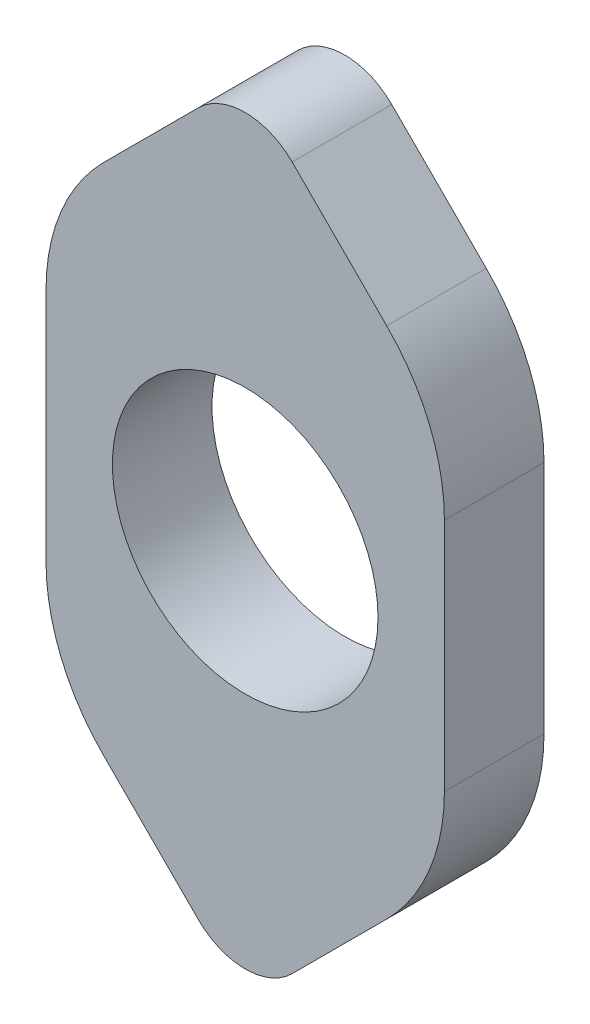
SolidWorks part; units mm, degrees
ref_plane "Спереди" through (0, 0, 0) normal (0, 0, 1) x (1, 0, 0)
ref_plane "Сверху" through (0, 0, 0) normal (0, 1, 0) x (1, 0, 0)
ref_plane "Справа" through (0, 0, 0) normal (1, 0, 0) x (0, 0, -1)
sketch "Эскиз1" plane through (0, 0, 0) normal (0, 0, 1) x (1, 0, 0)
  line L0 (1.1624, 13.6702) -> (1.1624, 2.4987) construction
  line L5 (-1.8376, 9.8546) -> (-1.8376, 6.3143)
  line L8 (4.1624, 9.8546) -> (4.1624, 6.3143)
  line L13 (1.8695, 13.3774) -> (3.2927, 11.9541)
  line L14 (1.8695, 2.7916) -> (3.2927, 4.2148)
  line L15 (0.4553, 13.3774) -> (-0.968, 11.9541)
  line L16 (0.4553, 2.7916) -> (-0.968, 4.2148)
  line L17 (1.1624, 14.0845) -> (1.1624, 2.0845) construction
  line L18 (4.1624, 14.0845) -> (4.1624, 2.0845) construction
  line L19 (-1.8376, 14.0845) -> (-1.8376, 2.0845) construction
  circle A7 centre (1.1624, 8.0845) radius 2
  arc A9 (1.8695, 13.3774) -> (0.4553, 13.3774) centre (1.1624, 12.6702) ccw
  arc A10 (0.4553, 2.7916) -> (1.8695, 2.7916) centre (1.1624, 3.4987) ccw
  arc A12 (-1.8376, 6.3143) -> (-0.968, 4.2148) centre (1.1314, 6.3143) ccw
  arc A13 (-1.8376, 9.8546) -> (-0.968, 11.9541) centre (1.1314, 9.8546) cw
  arc A14 (3.2927, 11.9541) -> (4.1624, 9.8546) centre (1.1933, 9.8546) cw
  arc A15 (3.2927, 4.2148) -> (4.1624, 6.3143) centre (1.1933, 6.3143) ccw
  dimension "D1" = 4
  dimension "D3" = 3
  dimension "D7" = 2
  dimension "D8" = 2
  dimension "D6" = 2.9691
  dimension "D4" = 3
extrude "Бобышка-Вытянуть1" add sketch "Эскиз1" along normal mid plane 1.5
